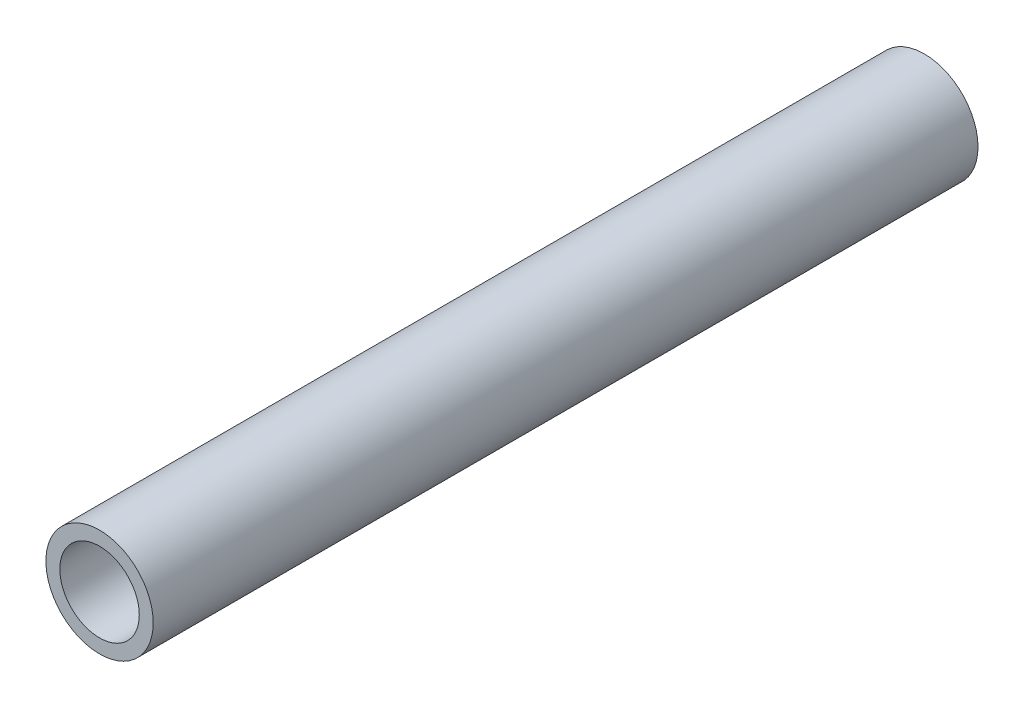
SolidWorks part; units mm, degrees
ref_plane "Front Plane" through (0, 0, 0) normal (0, 0, 1) x (1, 0, 0)
ref_plane "Top Plane" through (0, 0, 0) normal (0, 1, 0) x (1, 0, 0)
ref_plane "Right Plane" through (0, 0, 0) normal (1, 0, 0) x (0, 0, -1)
sketch "Sketch1" plane through (0, 0, 0) normal (0, 0, 1) x (1, 0, 0)
  circle A0 centre (0, 0) radius 10.668
  dimension "Pipe OD" = 21.336
extrude "Extrude-Thin1" add sketch "Sketch1" along normal mid plane 164 thin thin type one direction reverse wall 2.7686
